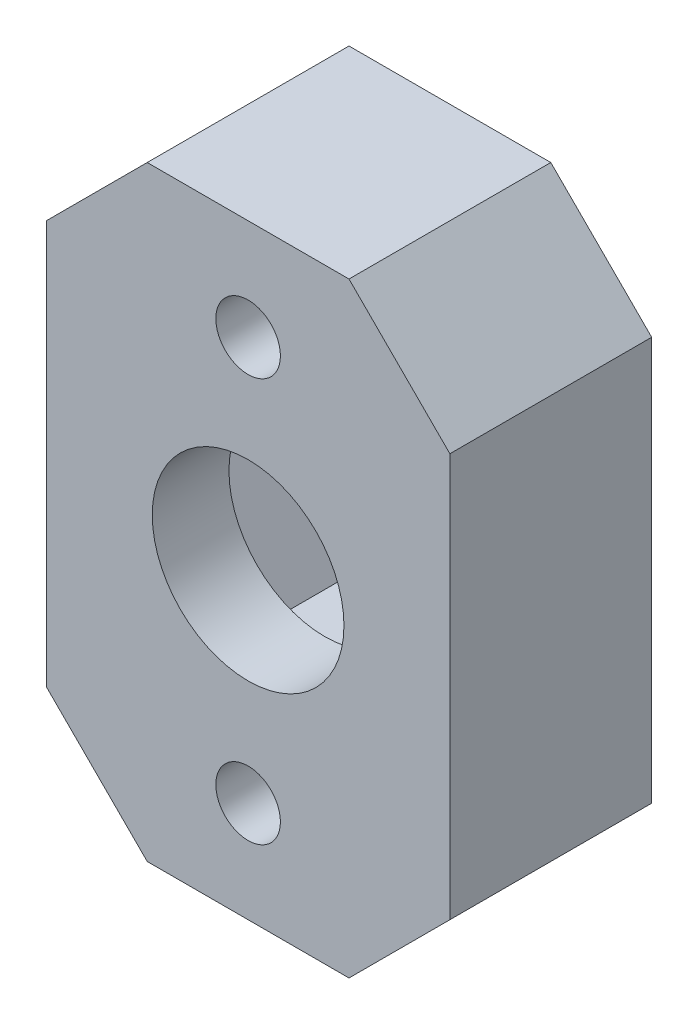
SolidWorks part; units mm, degrees
ref_plane "前基準面" through (0, 0, 0) normal (0, 0, 1) x (1, 0, 0)
ref_plane "上基準面" through (0, 0, 0) normal (0, 1, 0) x (1, 0, 0)
ref_plane "右基準面" through (0, 0, 0) normal (1, 0, 0) x (0, 0, -1)
sketch "草圖1" plane through (0, 0, 0) normal (0, 0, 1) x (1, 0, 0)
  line L1 (-10, 15) -> (10, 15)
  line L2 (-10, 15) -> (-10, -15)
  line L3 (-10, -15) -> (10, -15)
  line L4 (10, 15) -> (10, -15)
  line L5 (-10, 15) -> (10, -15) construction
  line L6 (-10, -15) -> (10, 15) construction
  line L7 (7.4478, 0) -> (3.7239, 6.45)
  line L8 (3.7239, 6.45) -> (-3.7239, 6.45)
  line L9 (-3.7239, 6.45) -> (-7.4478, 0)
  line L10 (-7.4478, 0) -> (-3.7239, -6.45)
  line L11 (-3.7239, -6.45) -> (3.7239, -6.45)
  line L12 (3.7239, -6.45) -> (7.4478, 0)
  circle A0 centre (0, 0) radius 6.45 construction
  circle A1 centre (0, 10) radius 1.6
  circle A2 centre (0, -10) radius 1.6
  point P0 (0, 0)
  point P20 (1.8076, -8.5863)
  point P21 (-1.3016, 0.2893)
  dimension "D4" = 10
  dimension "D5" = 10
  dimension "D6" = 3.2
  dimension "D7" = 3.2
  dimension "D1" = 20
  dimension "D2" = 30
  dimension "D3" = 12.9
extrude "填料-伸長1" add sketch "草圖1" along normal blind 10
chamfer "導角1" distance 5 angle 45 4 edges at (-10, -15, 5) (10, -15, 5) (10, 15, 5) (-10, 15, 5)
sketch "草圖2" plane through (0, 0, 10) normal (0, 0, 1) x (1, 0, 0)
  line L1 (-7.5, 7.5) -> (7.5, 7.5)
  line L2 (-7.5, 7.5) -> (-7.5, -7.5)
  line L3 (-7.5, -7.5) -> (7.5, -7.5)
  line L4 (7.5, 7.5) -> (7.5, -7.5)
  line L5 (-7.5, 7.5) -> (7.5, -7.5) construction
  line L6 (-7.5, -7.5) -> (7.5, 7.5) construction
  circle A0 centre (0, 0) radius 4.75
  point P0 (0, 0)
  dimension "D3" = 9.5
  dimension "D1" = 15
  dimension "D2" = 15
extrude "填料-伸長2" add sketch "草圖2" against normal blind 3.8
